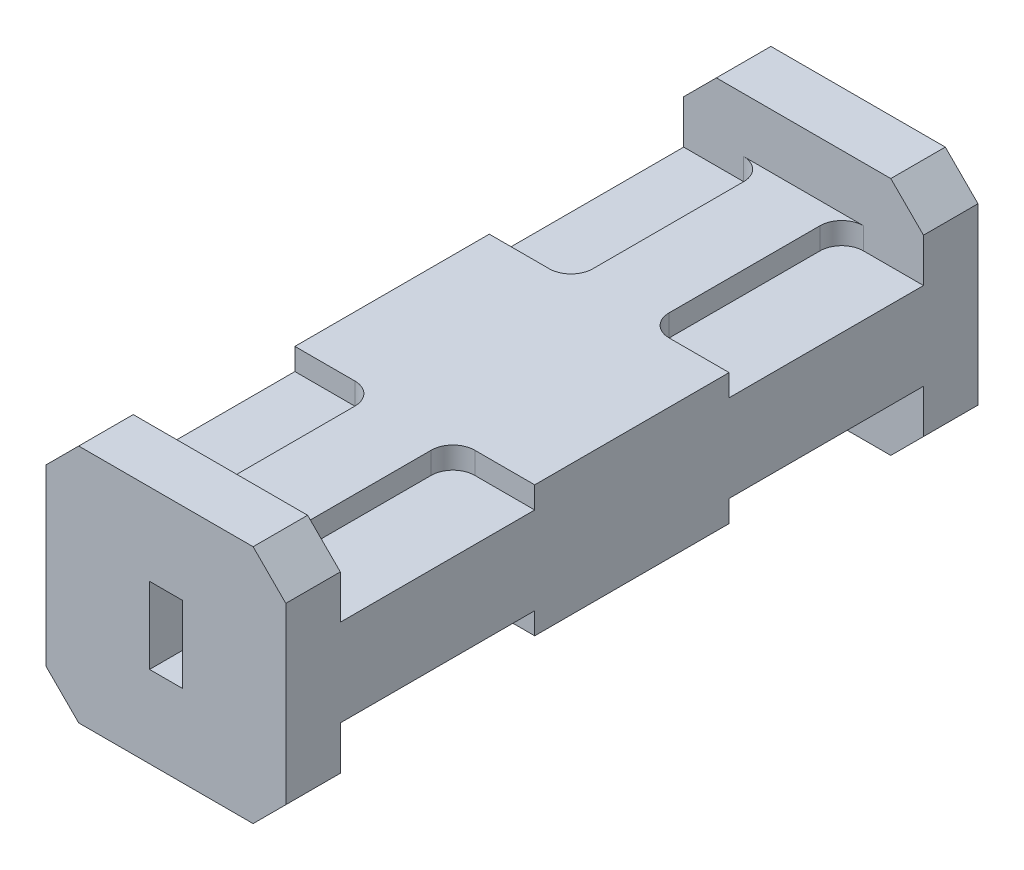
SolidWorks part; units mm, degrees
ref_plane "Front Plane" through (0, 0, 0) normal (0, 0, 1) x (1, 0, 0)
ref_plane "Top Plane" through (0, 0, 0) normal (0, 1, 0) x (1, 0, 0)
ref_plane "Right Plane" through (0, 0, 0) normal (1, 0, 0) x (0, 0, -1)
sketch "Sketch1" plane through (0, 0, 0) normal (0, 0, 1) x (1, 0, 0)
  line L1 (0, 0) -> (22, 0)
  line L2 (0, 0) -> (0, 22)
  line L3 (0, 22) -> (22, 22)
  line L4 (22, 0) -> (22, 22)
  dimension "D1" = 22
extrude "Boss-Extrude1" add sketch "Sketch1" against normal blind 63.5
sketch "Sketch2" plane through (22, 0, 0) normal (1, 0, 0) x (0, 0, -1)
  line L0 (0, 22) -> (5, 22) construction
  line L1 (63.5, 22) -> (0, 22) construction
  line L2 (63.5, 22) -> (58.5, 22) construction
  line L3 (5, 22) -> (5, 15)
  line L4 (0, 11) -> (63.5, 11) construction
  line L5 (0, 0) -> (0, 22) construction
  line L6 (63.5, 0) -> (63.5, 22) construction
  line L7 (31.75, 11) -> (31.75, 22) construction
  line L8 (5, 15) -> (22.8333, 15)
  line L9 (22.8333, 15) -> (22.8333, 17)
  line L10 (22.8333, 17) -> (40.6667, 17)
  line L11 (5, 22) -> (58.5, 22)
  line L12 (40.6667, 15) -> (40.6667, 17)
  line L13 (58.5, 15) -> (40.6667, 15)
  line L14 (58.5, 22) -> (58.5, 15)
  line L15 (22.8333, 7) -> (22.8333, 5)
  line L16 (5, 7) -> (22.8333, 7)
  line L17 (5, 0) -> (5, 7)
  line L18 (5, 0) -> (58.5, 0)
  line L19 (58.5, 0) -> (58.5, 7)
  line L20 (58.5, 7) -> (40.6667, 7)
  line L21 (40.6667, 7) -> (40.6667, 5)
  line L22 (22.8333, 5) -> (40.6667, 5)
  point P21 (31.75, 17)
  dimension "D1" = 5
  dimension "D2" = 7
  dimension "D3" = 2
extrude "Cut-Extrude1" cut sketch "Sketch2" against normal through all
sketch "Sketch3" plane through (0, 0, 0) normal (0, 0, 1) x (1, 0, 0)
  line L0 (0, 11) -> (22, 11) construction
  line L1 (0, 22) -> (0, 0) construction
  line L2 (22, 0) -> (22, 22) construction
  line L4 (9.5, 7.5) -> (12.5, 7.5)
  line L5 (9.5, 7.5) -> (9.5, 14.5)
  line L6 (9.5, 14.5) -> (12.5, 14.5)
  line L7 (12.5, 7.5) -> (12.5, 14.5)
  line L8 (9.5, 7.5) -> (12.5, 14.5) construction
  line L9 (9.5, 14.5) -> (12.5, 7.5) construction
  point P6 (11, 11)
  dimension "D1" = 7
  dimension "D2" = 3
extrude "Cut-Extrude2" cut sketch "Sketch3" against normal through all
sketch "Sketch4" plane through (0, 0, -5) normal (0, 0, -1) x (-1, 0, 0)
  line L0 (-11, 15) -> (-11, 22) construction
  line L1 (0, 15) -> (-22, 15) construction
  line L2 (0, 22) -> (-22, 22) construction
  line L3 (-14.5, 17) -> (-7.5, 17)
  line L4 (-14.5, 17) -> (-14.5, 15)
  line L5 (-14.5, 15) -> (-7.5, 15)
  line L6 (-7.5, 15) -> (-7.5, 17)
  point P9 (-11, 17)
  dimension "D1" = 2
  dimension "D2" = 7
extrude "Boss-Extrude2" add sketch "Sketch4" along normal up to surface (53.5 mm away) up to face at (11, 18.5, -58.5)
ref_plane "Plane1" through (0, 11, 0) normal (0, 1, 0) x (1, 0, 0)
mirror "Mirror1" about plane through (0, 11, 0) normal (0, 1, 0) of "Boss-Extrude2"
fillet "Fillet1" radius 2 16 edges at (14.5, 6, -40.6667) (14.5, 6, -5) (14.5, 6, -22.8333) (14.5, 6, -58.5) (7.5, 6, -58.5) (7.5, 6, -22.8333) (7.5, 6, -40.6667) (7.5, 6, -5) (7.5, 16, -5) (7.5, 16, -22.8333) (7.5, 16, -40.6667) (7.5, 16, -58.5) (14.5, 16, -58.5) (14.5, 16, -40.6667) (14.5, 16, -5) (14.5, 16, -22.8333)
chamfer "Chamfer1" distance 3 angle 45 8 edges at (0, 0, -61) (0, 22, -61) (22, 22, -61) (22, 0, -61) (22, 0, -2.5) (0, 0, -2.5) (0, 22, -2.5) (22, 22, -2.5)
